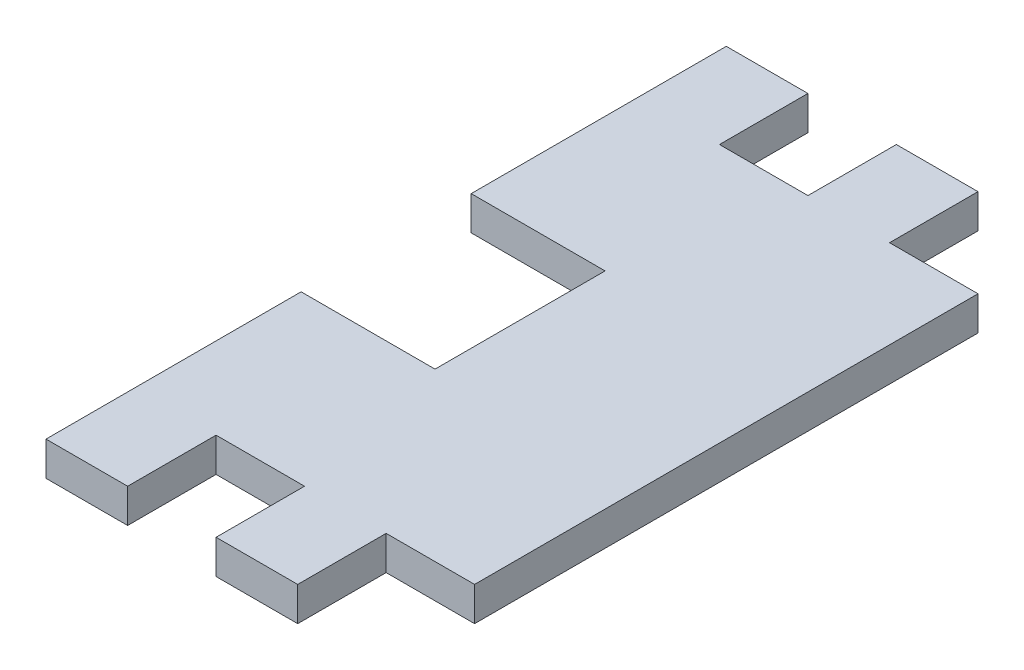
SolidWorks part; units mm, degrees
ref_plane "Front Plane" through (0, 0, 0) normal (0, 0, 1) x (1, 0, 0)
ref_plane "Top Plane" through (0, 0, 0) normal (0, 1, 0) x (1, 0, 0)
ref_plane "Right Plane" through (0, 0, 0) normal (1, 0, 0) x (0, 0, -1)
sketch "Sketch1" plane through (0, 0, 0) normal (0, 1, 0) x (1, 0, 0)
  line L0 (0, 0) -> (-44.1011, 0) construction
  line L1 (0, -25.4) -> (0, 25.4)
  line L2 (0, 25.4) -> (-25.4, 25.4)
  line L3 (-25.4, 25.4) -> (-25.4, 6.35)
  line L4 (-25.4, 6.35) -> (-15.4, 6.35)
  line L5 (-15.4, 6.35) -> (-15.4, -6.35)
  line L7 (-25.4, -6.35) -> (-15.4, -6.35)
  line L8 (-25.4, -25.4) -> (-25.4, -6.35)
  line L9 (0, -25.4) -> (-25.4, -25.4)
  dimension "D1" = 50.8
  dimension "D2" = 10
  dimension "D3" = 12.7
  dimension "D4" = 25.4
extrude "Boss-Extrude1" add sketch "Sketch1" along normal mid plane 2.54
sketch "Sketch2" plane through (0, 1.27, 0) normal (0, 1, 0) x (1, 0, 0)
  line L0 (0, 25.4) -> (-25.4, 25.4) construction
  line L1 (0, 25.4) -> (-6.604, 25.4)
  line L2 (0, 25.4) -> (0, 18.796)
  line L3 (0, 18.796) -> (-6.604, 18.796)
  line L4 (-6.604, 25.4) -> (-6.604, 18.796)
  line L5 (0, -25.4) -> (0, 25.4) construction
  line L6 (-12.7, 25.4) -> (-19.304, 25.4)
  line L7 (-12.7, 25.4) -> (-12.7, 18.796)
  line L8 (-12.7, 18.796) -> (-19.304, 18.796)
  line L9 (-19.304, 25.4) -> (-19.304, 18.796)
  line L10 (0, 0) -> (-15.4, 0) construction
  line L11 (-15.4, 6.35) -> (-15.4, -6.35) construction
  line L12 (-19.304, -25.4) -> (-19.304, -18.796)
  line L13 (-12.7, -18.796) -> (-19.304, -18.796)
  line L14 (-12.7, -25.4) -> (-12.7, -18.796)
  line L15 (-12.7, -25.4) -> (-19.304, -25.4)
  line L16 (-6.604, -25.4) -> (-6.604, -18.796)
  line L17 (0, -18.796) -> (-6.604, -18.796)
  line L18 (0, -25.4) -> (0, -18.796)
  line L19 (0, -25.4) -> (-6.604, -25.4)
  dimension "D1" = 6.604
  dimension "D2" = 6.604
  dimension "D3" = 2
extrude "Cut-Extrude1" cut sketch "Sketch2" against normal through all
